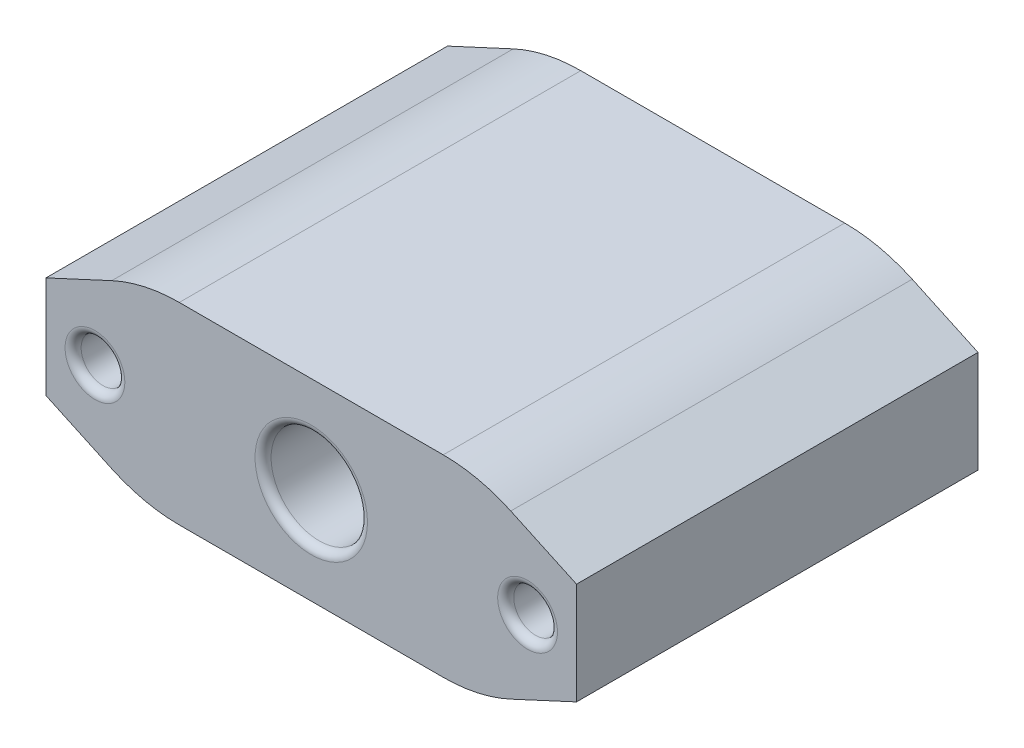
SolidWorks part; units mm, degrees
ref_plane "Front Plane" through (0, 0, 0) normal (0, 0, 1) x (1, 0, 0)
ref_plane "Top Plane" through (0, 0, 0) normal (0, 1, 0) x (1, 0, 0)
ref_plane "Right Plane" through (0, 0, 0) normal (1, 0, 0) x (0, 0, -1)
sketch "Sketch1" plane through (0, 0, 0) normal (0, 0, 1) x (-1, 0, 0)
  line L27 (16.518, 3.175) -> (16.518, -3.175)
  line L28 (10.422, -3.175) -> (10.422, 3.175) construction
  line L29 (16.518, -3.175) -> (10.422, -3.175) construction
  line L30 (16.518, 3.175) -> (10.422, 3.175) construction
  line L31 (10.422, -3.175) -> (10.422, -6) construction
  line L32 (10.422, -3.175) -> (16.518, 3.175) construction
  line L33 (10.422, 3.175) -> (16.518, -3.175) construction
  line L34 (0, -6) -> (0, 6) construction
  line L35 (10.422, -6) -> (-10.422, -6)
  line L36 (10.422, 3.175) -> (10.422, 6) construction
  line L37 (10.422, 6) -> (-10.422, 6)
  line L38 (-13.47, 0) -> (13.47, 0) construction
  line L39 (16.518, -3.175) -> (10.422, -6)
  line L40 (16.518, 3.175) -> (10.422, 6)
  line L41 (-16.518, -3.175) -> (-10.422, -3.175) construction
  line L42 (-10.422, -3.175) -> (-10.422, 3.175) construction
  line L43 (-10.422, -3.175) -> (-16.518, 3.175) construction
  line L44 (-10.422, 3.175) -> (-16.518, -3.175) construction
  line L45 (-16.518, 3.175) -> (-10.422, 3.175) construction
  line L46 (-10.422, 3.175) -> (-10.422, 6) construction
  line L47 (-10.422, -3.175) -> (-10.422, -6) construction
  line L48 (-16.518, 3.175) -> (-16.518, -3.175)
  line L49 (-16.518, 3.175) -> (-10.422, 6)
  line L50 (-16.518, -3.175) -> (-10.422, -6)
  circle A3 centre (13.47, 0) radius 1.3609
  circle A4 centre (-13.47, 0) radius 1.3609
  circle A5 centre (0, 0) radius 3
  point P44 (0, 0)
  dimension "D7" = 6
  dimension "D8" = 2.7219
  dimension "D9" = 20.8439
  dimension "D5" = 33.0359
  dimension "D6" = 12
  dimension "D10" = 6.35
extrude "Boss-Extrude1" add sketch "Sketch1" along normal blind 25
fillet "Fillet1" radius 10 1 edges at (-10.422, 6, 12.5)
fillet "Fillet2" radius 10 1 edges at (-10.422, -6, 12.5)
fillet "Fillet4" radius 10 1 edges at (10.422, -6, 12.5)
fillet "Fillet5" radius 10 1 edges at (10.422, 6, 12.5)
fillet "Fillet8" radius 0.5 1 edges at (3, 0, 0)
fillet "Fillet9" radius 0.5 1 edges at (12.109, 0, 0)
fillet "Fillet10" radius 0.5 1 edges at (-12.109, 0, 0)
fillet "Fillet11" radius 0.5 1 edges at (3, 0, 25)
fillet "Fillet12" radius 0.5 1 edges at (12.109, 0, 25)
fillet "Fillet13" radius 0.5 1 edges at (-12.109, 0, 25)
